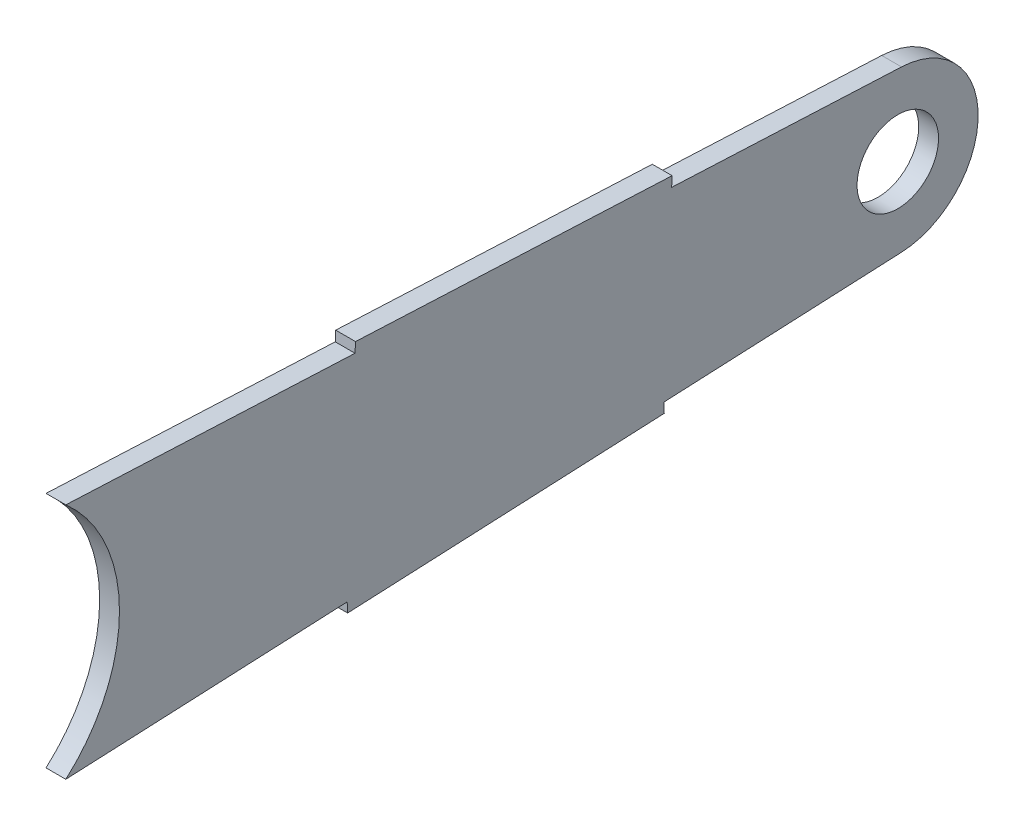
SolidWorks part; units mm, degrees
material "AISI 4130 Steel, annealed at 865C"
ref_plane "X-Y Datum" through (0, 0, 0) normal (0, 0, 1) x (1, 0, 0)
ref_plane "X-Z Datum" through (0, 0, 0) normal (0, 1, 0) x (1, 0, 0)
ref_plane "Y-Z Datum" through (0, 0, 0) normal (1, 0, 0) x (0, 0, -1)
sketch "Sketch1" plane through (0, 0, 0) normal (1, 0, 0) x (0, 0, -1)
  line L0 (0, 0) -> (-66.675, 0) construction
  line L1 (-66.675, 9.525) -> (-66.675, -9.525)
  line L2 (0.297, 6.432) -> (-66.675, 9.525)
  line L3 (0.297, -6.432) -> (-66.675, -9.525)
  line L4 (-66.675, 0) -> (-75.0753, 0) construction
  line L5 (0.297, 6.432) -> (-18.1227, 7.2827)
  line L6 (-43.459, 9.2474) -> (-18.0861, 8.0756)
  line L7 (-43.459, 9.2474) -> (-43.5323, 7.6616)
  line L8 (-18.0861, 8.0756) -> (-18.1593, 6.4898)
  line L9 (-43.5323, 7.6616) -> (-18.1593, 6.4898)
  line L10 (-43.459, 9.2474) -> (-18.1593, 6.4898) construction
  line L11 (-18.0861, 8.0756) -> (-43.5323, 7.6616) construction
  line L12 (0.297, -6.432) -> (-18.753, -7.3118)
  line L13 (-44.0892, -9.2774) -> (-18.7163, -8.1056)
  line L14 (-44.0892, -9.2774) -> (-44.1626, -7.6899)
  line L15 (-18.7163, -8.1056) -> (-18.7896, -6.5181)
  line L16 (-44.1626, -7.6899) -> (-18.7896, -6.5181)
  line L17 (-44.0892, -9.2774) -> (-18.7896, -6.5181) construction
  line L18 (-18.7163, -8.1056) -> (-44.1626, -7.6899) construction
  circle A0 centre (0, 0) radius 3.2639
  arc A1 (0.297, -6.432) -> (0.297, 6.432) centre (0, 0) ccw
  circle A2 centre (-66.675, 9.525) radius 12.7 construction
  circle A3 centre (-66.675, -9.525) radius 12.7 construction
  circle A4 centre (-75.0753, 0) radius 12.7
  point P7 (-66.675, 0)
  point P15 (-30.8092, 7.8686)
  point P16 (-31.4394, -7.8977)
  dimension "D1" = 6.5278
  dimension "D2" = 3.175
  dimension "D5" = 18.4394
  dimension "D3" = 66.675
  dimension "D4" = 19.05
  dimension "D6" = 1.5875
  dimension "D7" = 25.4
  dimension "D8" = 19.05
  dimension "D9" = 25.4
  dimension "D10" = 1.5875
extrude "Boss-Extrude1" add sketch "Sketch1" along normal mid plane 1.5875 contours A4 L3 A1 L2 A0 | L13 L15 L3 L14 | L16 L14 L3 L15 | L6 L8 L9 L7
